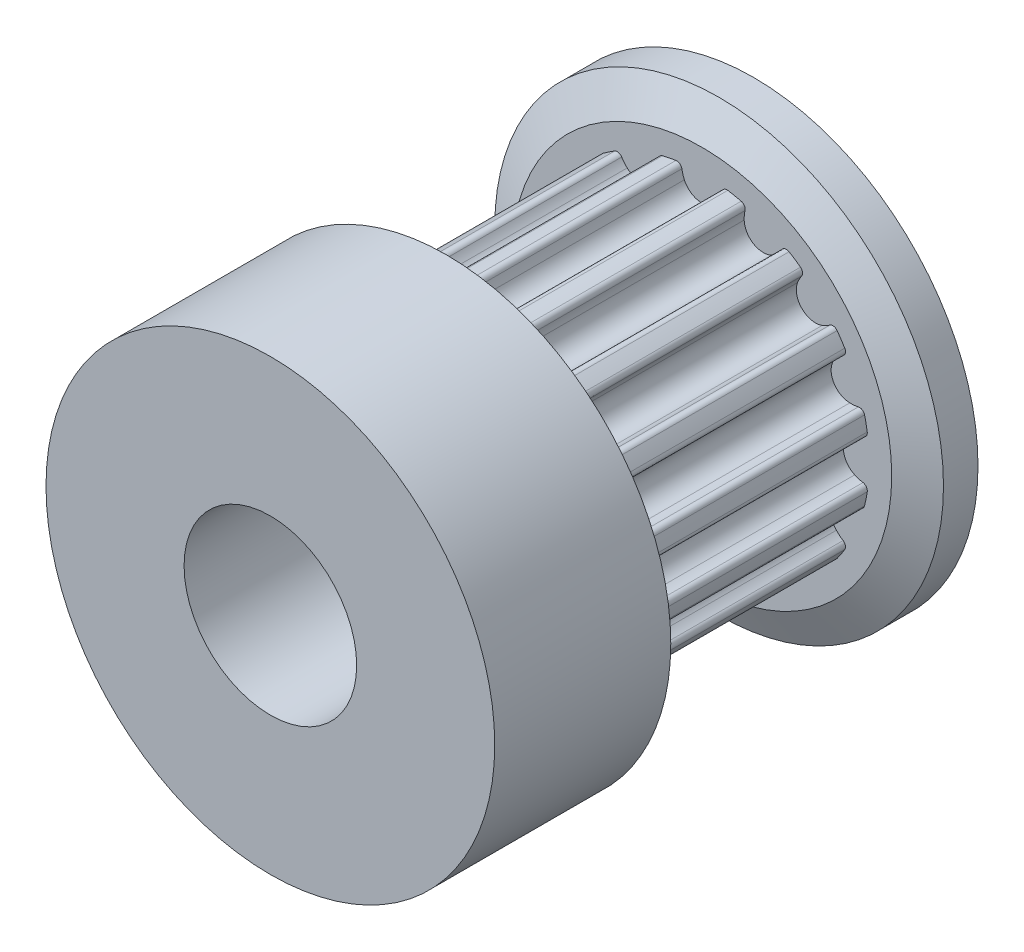
SolidWorks part; units mm, degrees
ref_plane "Front Plane" through (0, 0, 0) normal (0, 0, 1) x (1, 0, 0)
ref_plane "Top Plane" through (0, 0, 0) normal (0, 1, 0) x (1, 0, 0)
ref_plane "Right Plane" through (0, 0, 0) normal (1, 0, 0) x (0, 0, -1)
sketch "Sketch1" plane through (0, 0, 0) normal (0, 0, 1) x (1, 0, 0)
  circle A0 centre (0, 0) radius 4.85
  dimension "D1" = 9.7
extrude "Base" add sketch "Sketch1" along normal blind 7.4
sketch "Sketch2" plane through (0, 0, 7.4) normal (0, 0, 1) x (1, 0, 0)
  line L0 (0, 0) -> (0, 4.85) construction
  line L1 (0, 0) -> (-1.928, 5.9336) construction
  line L2 (-0.7587, 4.7903) -> (-0.7898, 5.545)
  line L5 (-0.7898, 5.545) -> (0.9207, 5.545)
  line L6 (0.9207, 5.545) -> (0.7587, 4.7903)
  arc A1 (-0.5796, 4.6686) -> (-0.5066, 4.4283) centre (0.4062, 4.8368) ccw
  arc A2 (-0.5066, 4.4283) -> (0.5066, 4.4283) centre (0, 4.655) ccw
  arc A3 (-0.5796, 4.6686) -> (-0.7507, 4.7916) centre (-0.7274, 4.6434) ccw
  arc A4 (0.5796, 4.6686) -> (0.5066, 4.4283) centre (-0.4062, 4.8368) cw
  arc A5 (0.5796, 4.6686) -> (0.7507, 4.7916) centre (0.7274, 4.6434) cw
  arc A6 (0.7507, 4.7916) -> (0.7587, 4.7903) centre (0, 0) cw
  arc A11 (-0.7507, 4.7916) -> (-0.7587, 4.7903) centre (0, 0) ccw
  dimension "D1" = 4.85
  dimension "D3" = 2
  dimension "D4" = 1.11
  dimension "D7" = 0.3
  dimension "D2" = 18
  dimension "D5" = 0.195
  dimension "D8" = 0.4062
extrude "ToothCut" cut sketch "Sketch2" against normal through all
pattern_circular "TeethCuts" count 16 over 360 about axis through (0, 0, 0) along (0, 0, 1) of "ToothCut"
sketch "Sketch3" plane through (0, 0, 0) normal (0, 1, 0) x (1, 0, 0)
  line L0 (0, 0) -> (0, 1.5)
  line L1 (0, 1.5) -> (-6.5, 1.5)
  line L2 (-6.5, 1.5) -> (-6.5, 0.5)
  line L3 (-5.5, 0) -> (0, 0)
  line L4 (0, -7.4) -> (-6.5, -7.4)
  line L5 (-0.5066, -7.4) -> (0.5066, -7.4) construction
  line L6 (-6.5, -7.4) -> (-6.5, -12.5)
  line L7 (-6.5, -12.5) -> (0, -12.5)
  line L8 (0, -12.5) -> (0, -7.4)
  line L9 (-6.5, 0.5) -> (-5.5, 0)
  point P5 (-6.5, 0)
  dimension "D1" = 14
  dimension "D2" = 1.5
  dimension "D3" = 0.5
  dimension "D4" = 1
  dimension "D5" = 6.5
revolve "Body" add sketch "Sketch3" angle 360 about L8
sketch "Sketch4" plane through (0, 0, 0) normal (0, 0, 1) x (1, 0, 0)
  circle A0 centre (0, 0) radius 2.5
  dimension "D1" = 5
extrude "ShaftHole" cut sketch "Sketch4" along normal through all both and the other way through all
sketch "Sketch5" plane through (0, 0, 0) normal (0, 1, 0) x (1, 0, 0)
  line L0 (-6.5, -7.4) -> (-6.5, -12.5) construction
  line L3 (-6.5, -12.5) -> (6.5, -12.5) construction
  circle A0 centre (1.5, -8.95) radius 2
  dimension "D1" = 4
  dimension "D2" = 8
  dimension "D3" = 3.55
